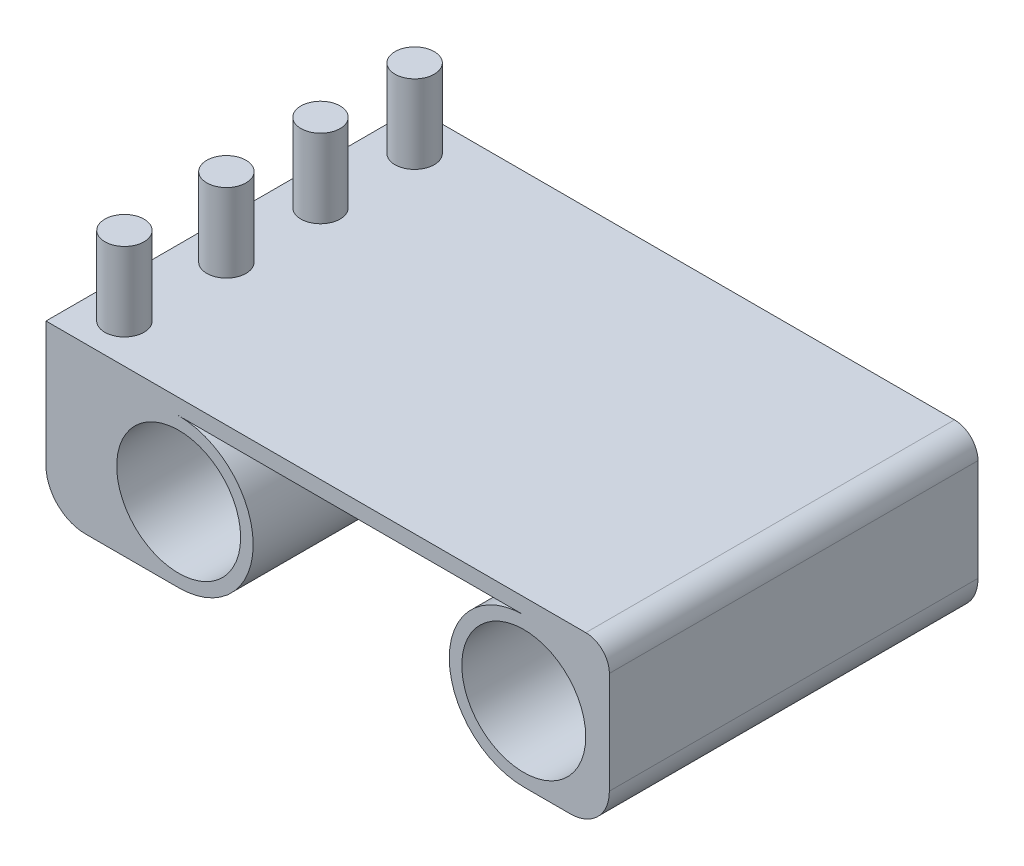
SolidWorks part; units mm, degrees
ref_plane "Plan de face" through (0, 0, 0) normal (0, 0, 1) x (1, 0, 0)
ref_plane "Plan de dessus" through (0, 0, 0) normal (0, 1, 0) x (1, 0, 0)
ref_plane "Plan de droite" through (0, 0, 0) normal (1, 0, 0) x (0, 0, -1)
sketch "Esquisse1" plane through (0, 0, 0) normal (0, 0, 1) x (1, 0, 0)
  line L0 (5.271, 19) -> (49.271, 19)
  line L1 (0, 0) -> (60.1842, 0)
  line L2 (0, 0) -> (-11.6423, 0)
  line L3 (0, 21) -> (60.1842, 21)
  line L4 (60.1842, 0) -> (60.1842, 21)
  line L10 (-11.6423, 0) -> (-11.6423, 21)
  line L11 (-11.6423, 21) -> (0, 21)
  circle A0 centre (5.271, 9.5) radius 7.9
  circle A1 centre (5.271, 9.5) radius 9.5
  circle A2 centre (49.271, 9.5) radius 7.9
  circle A3 centre (49.271, 9.5) radius 9.5
  dimension "D3" = 19
  dimension "D4" = 19
  dimension "D5" = 15.8
  dimension "D6" = 15.8
  dimension "D2" = 44
  dimension "D7" = 9.5
  dimension "D10" = 2
extrude "Boss.-Extru.1" add sketch "Esquisse1" along normal blind 47
fillet "Congé1" radius 5 1 edges at (-11.6423, 0, 23.5)
fillet "Congé2" radius 5 1 edges at (60.1842, 0, 23.5)
fillet "Congé4" radius 3 1 edges at (60.1842, 21, 23.5)
sketch "Esquisse2" plane through (0, 21, 0) normal (0, 1, 0) x (1, 0, 0)
  line L0 (-11.6423, -47) -> (-11.6423, 0) construction
  line L1 (-11.6423, -47) -> (57.1842, -47) construction
  line L2 (-11.6423, 0) -> (57.1842, 0) construction
  circle A0 centre (-6.6423, -42) radius 2.5
  circle A1 centre (-6.6423, -29) radius 2.5
  circle A2 centre (-6.6423, -17) radius 2.5
  circle A3 centre (-6.6423, -5) radius 2.5
  dimension "D1" = 5
  dimension "D2" = 5
  dimension "D3" = 5
  dimension "D4" = 5
  dimension "D5" = 5
  dimension "D6" = 5
  dimension "D7" = 5
  dimension "D8" = 5
  dimension "D9" = 5
  dimension "D10" = 5
  dimension "D11" = 12
  dimension "D12" = 12
extrude "Boss.-Extru.2" add sketch "Esquisse2" along normal blind 10
sketch "Esquisse3" plane through (-11.6423, 0, 0) normal (-1, 0, 0) x (0, 0, 1)
  line L0 (7.5, 21) -> (7.5, 31) construction
  line L1 (19.5, 21) -> (19.5, 31) construction
  line L2 (31.5, 21) -> (31.5, 31) construction
  line L3 (39.5, 31) -> (39.5, 21) construction
  line L4 (7.5, 21) -> (2.5, 21) construction
  line L5 (19.5, 21) -> (14.5, 21) construction
  line L6 (31.5, 21) -> (26.5, 21) construction
  line L7 (44.5, 21) -> (39.5, 21) construction
  circle A0 centre (5, 26) radius 1.5
  circle A1 centre (17, 26) radius 1.5
  circle A2 centre (29, 26) radius 1.5
  circle A3 centre (42, 26) radius 1.5
  dimension "D1" = 3
  dimension "D2" = 3
  dimension "D3" = 3
  dimension "D4" = 3
  dimension "D5" = 2.5
  dimension "D6" = 2.5
  dimension "D7" = 2.5
  dimension "D8" = 2.5
  dimension "D9" = 5
  dimension "D10" = 5
  dimension "D11" = 5
  dimension "D12" = 5
extrude "Enlèv. mat.-Extru.1" cut sketch "Esquisse3" against normal blind 6
